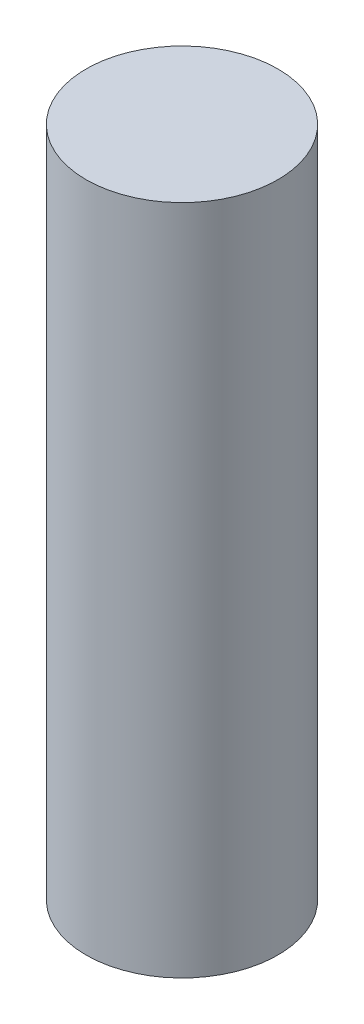
SolidWorks part; units mm, degrees
ref_plane "Piano frontale" through (0, 0, 0) normal (0, 0, 1) x (1, 0, 0)
ref_plane "Piano superiore" through (0, 0, 0) normal (0, 1, 0) x (1, 0, 0)
ref_plane "Piano destro" through (0, 0, 0) normal (1, 0, 0) x (0, 0, -1)
sketch "Schizzo1" plane through (0, 0, 0) normal (0, 1, 0) x (1, 0, 0)
  circle A0 centre (-6.9304, 2.146) radius 1
  dimension "D1" = 2
extrude "Estrusione-Estrusione1" add sketch "Schizzo1" along normal blind 7
